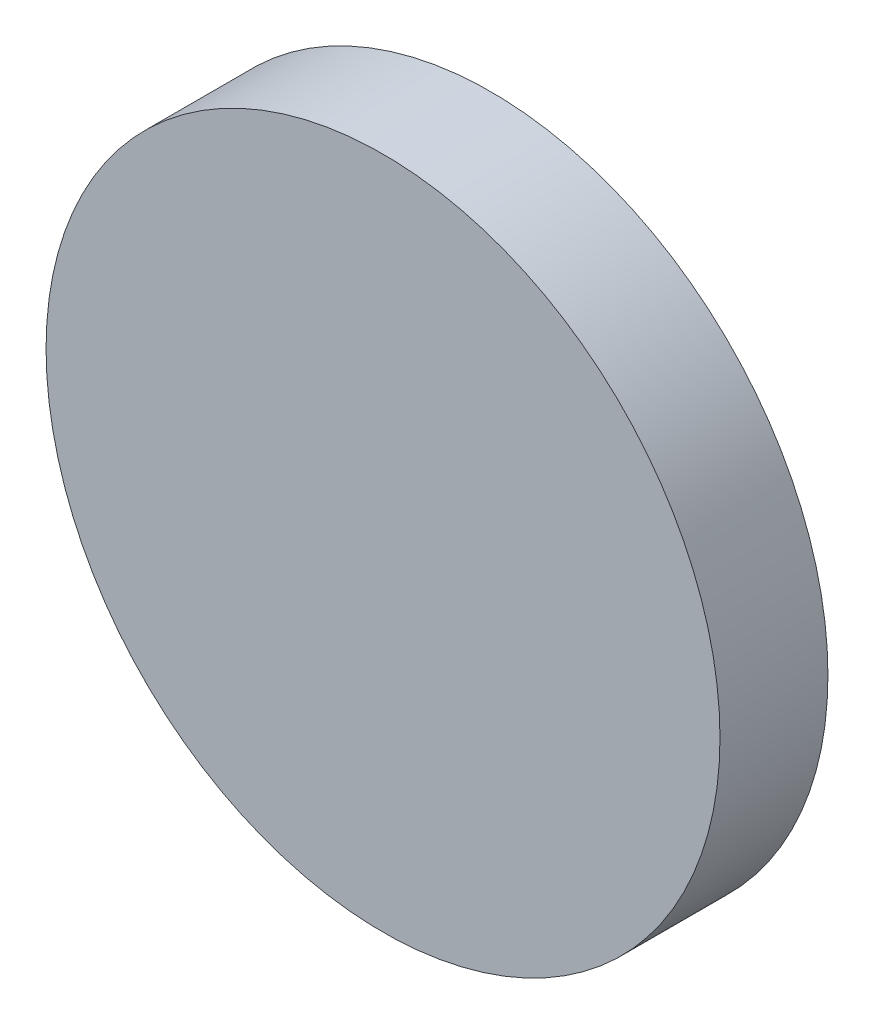
SolidWorks part; units mm, degrees
ref_plane "Front" through (0, 0, 0) normal (0, 0, 1) x (1, 0, 0)
ref_plane "Top" through (0, 0, 0) normal (0, 1, 0) x (1, 0, 0)
ref_plane "Right" through (0, 0, 0) normal (1, 0, 0) x (0, 0, -1)
sketch "Sketch1" plane through (0, 0, 0) normal (0, 0, 1) x (1, 0, 0)
  circle A0 centre (0, 0) radius 31.215
extrude "Boss-Extrude1" add sketch "Sketch1" along normal blind 10
